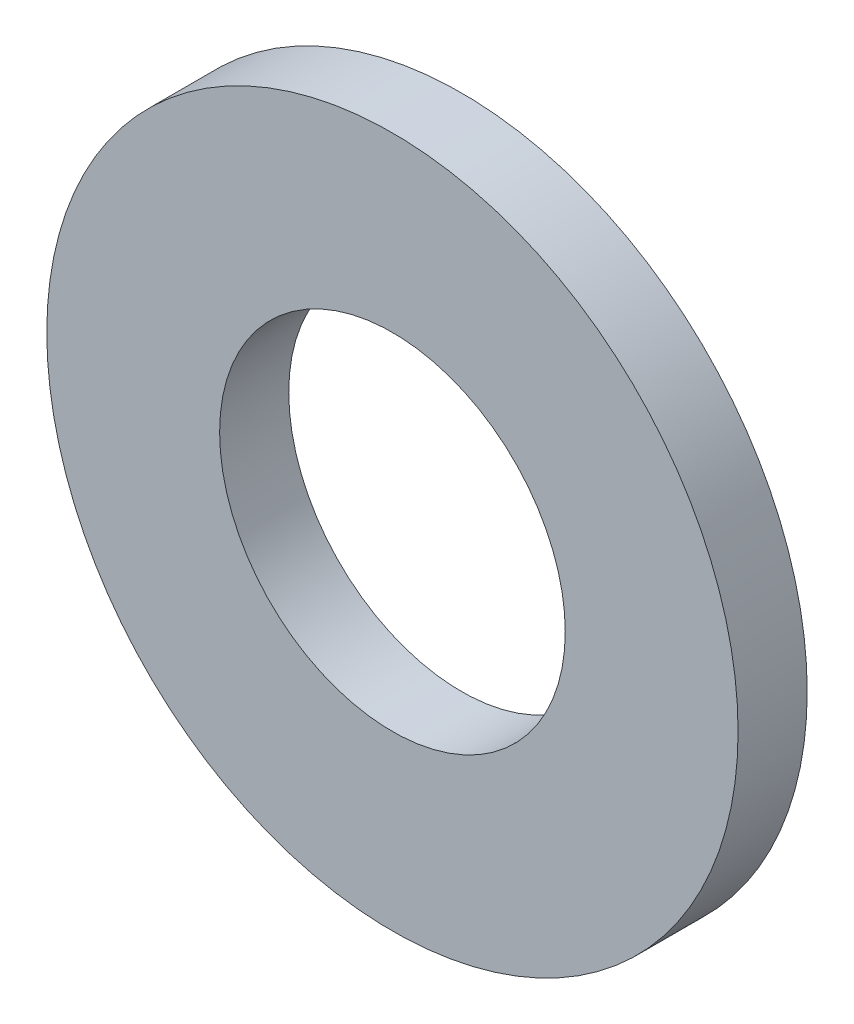
SolidWorks part; units mm, degrees
ref_plane "Plan de face" through (0, 0, 0) normal (0, 0, 1) x (1, 0, 0)
ref_plane "Plan de dessus" through (0, 0, 0) normal (0, 1, 0) x (1, 0, 0)
ref_plane "Plan de droite" through (0, 0, 0) normal (1, 0, 0) x (0, 0, -1)
sketch "Esquisse1" plane through (0, 0, 0) normal (0, 0, 1) x (1, 0, 0)
  circle A0 centre (0, 0) radius 6
  dimension "D1" = 12
extrude "Boss.-Extru.1" add sketch "Esquisse1" along normal blind 1.2
sketch "Esquisse2" plane through (0, 0, 1.2) normal (0, 0, 1) x (1, 0, 0)
  circle A0 centre (0, 0) radius 3
  dimension "D1" = 6
extrude "Enlèv. mat.-Extru.1" cut sketch "Esquisse2" against normal blind 1.2
